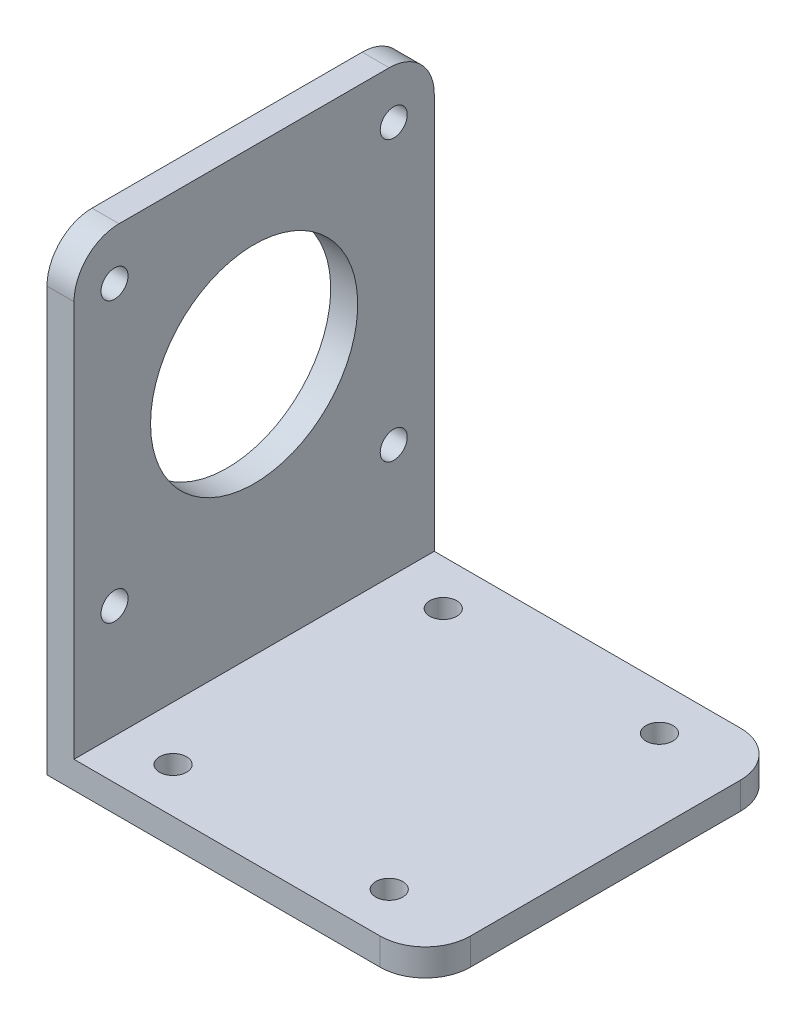
SolidWorks part; units mm, degrees
material "201.0-T43 绝缘成型铸件 (SS)"
ref_plane "前视基准面" through (0, 0, 0) normal (0, 0, 1) x (1, 0, 0)
ref_plane "上视基准面" through (0, 0, 0) normal (0, 1, 0) x (1, 0, 0)
ref_plane "右视基准面" through (0, 0, 0) normal (1, 0, 0) x (0, 0, -1)
other "Configuration Table"
sketch "草图1" plane through (0, 0, 0) normal (0, 1, 0) x (1, 0, 0)
  line L0 (0, 0) -> (0, 21.0256) construction
  line L1 (-21, -20) -> (21, -20)
  line L2 (-21, -20) -> (-21, 20)
  line L3 (-21, 20) -> (21, 20)
  line L4 (21, -20) -> (21, 20)
  line L5 (-21, -20) -> (21, 20) construction
  line L6 (-21, 20) -> (21, -20) construction
  line L7 (0, 0) -> (29.6049, 0) construction
  circle A0 centre (-12, 15) radius 1.5
  circle A1 centre (-12, -15) radius 1.5
  circle A2 centre (12, -15) radius 1.5
  circle A3 centre (12, 15) radius 1.5
  point P0 (0, 0)
  dimension "D3" = 3
  dimension "D1" = 42
  dimension "D2" = 40
  dimension "D4" = 30
  dimension "D5" = 24
extrude "凸台-拉伸1" add sketch "草图1" along normal blind 3
sketch "草图3" plane through (-21, 0, 0) normal (-1, 0, 0) x (0, 0, 1)
  line L0 (-20, 3) -> (-20, 52)
  line L1 (-20, 52) -> (20, 52)
  line L2 (20, 52) -> (20, 3)
  line L3 (0, 0) -> (0, 54.6661) construction
  line L4 (-20, 3) -> (20, 3)
  line L5 (-20, 0) -> (20, 0) construction
  circle A0 centre (0, 31) radius 11.5
  circle A1 centre (-15.5, 46.5) radius 1.5
  circle A2 centre (-15.5, 15.5) radius 1.5
  circle A3 centre (15.5, 15.5) radius 1.5
  circle A4 centre (15.5, 46.5) radius 1.5
  dimension "D2" = 23
  dimension "D3" = 3
  dimension "D4" = 3
  dimension "D1" = 49
  dimension "D5" = 31
  dimension "D6" = 31
  dimension "D7" = 15.5
  dimension "D8" = 15.5
  dimension "D9" = 31
extrude "凸台-拉伸2" add sketch "草图3" against normal blind 3
fillet "圆角1" radius 5 2 edges at (-19.5, 52, -20) (-19.5, 52, 20)
fillet "圆角2" radius 5 2 edges at (21, 1.5, -20) (21, 1.5, 20)
